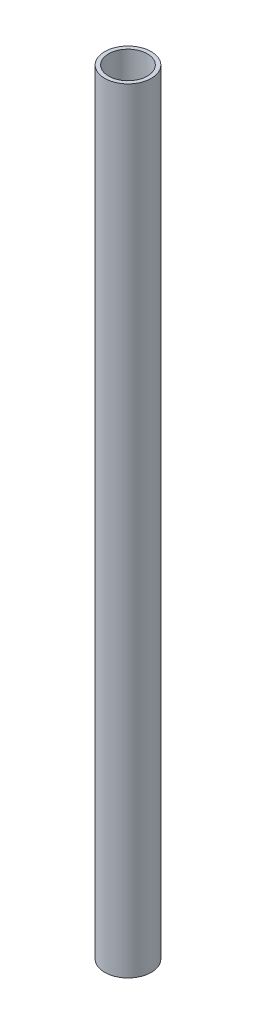
SolidWorks part; units mm, degrees
material "ABS PC"
ref_plane "Front Plane" through (0, 0, 0) normal (0, 0, 1) x (1, 0, 0)
ref_plane "Top Plane" through (0, 0, 0) normal (0, 1, 0) x (1, 0, 0)
ref_plane "Right Plane" through (0, 0, 0) normal (1, 0, 0) x (0, 0, -1)
sketch "Sketch1" plane through (0, 0, 0) normal (0, 1, 0) x (1, 0, 0)
  circle A0 centre (0, 0) radius 15
  circle A1 centre (0, 0) radius 12.5
  dimension "D1" = 30
  dimension "D2" = 25
extrude "Boss-Extrude1" add sketch "Sketch1" along normal blind 500
